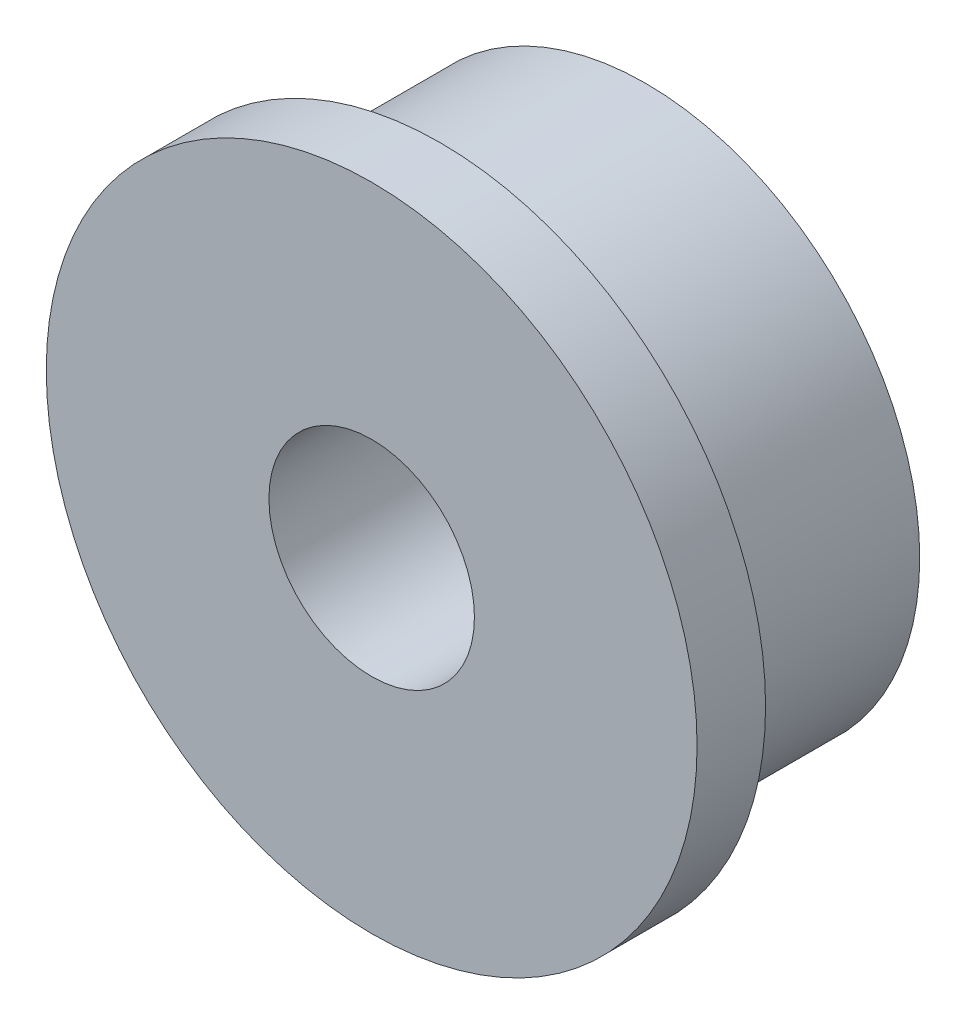
SolidWorks part; units mm, degrees
ref_plane "前视基准面" through (0, 0, 0) normal (0, 0, 1) x (1, 0, 0)
ref_plane "上视基准面" through (0, 0, 0) normal (0, 1, 0) x (1, 0, 0)
ref_plane "右视基准面" through (0, 0, 0) normal (1, 0, 0) x (0, 0, -1)
sketch "草图1" plane through (0, 0, 0) normal (0, 0, 1) x (1, 0, 0)
  circle A0 centre (0, 0) radius 4.75
  dimension "D1" = 9.5
extrude "凸台-拉伸1" add sketch "草图1" against normal blind 1
sketch "草图2" plane through (0, 0, 0) normal (0, 0, 1) x (1, 0, 0)
  circle A0 centre (0, 0) radius 4
  dimension "D1" = 8
extrude "凸台-拉伸2" add sketch "草图2" against normal blind 4
sketch "草图5" plane through (0, 0, 0) normal (0, 0, 1) x (1, 0, 0)
  circle A0 centre (0, 0) radius 1.5
  dimension "D1" = 3
extrude "切除-拉伸1" cut sketch "草图5" against normal through all
